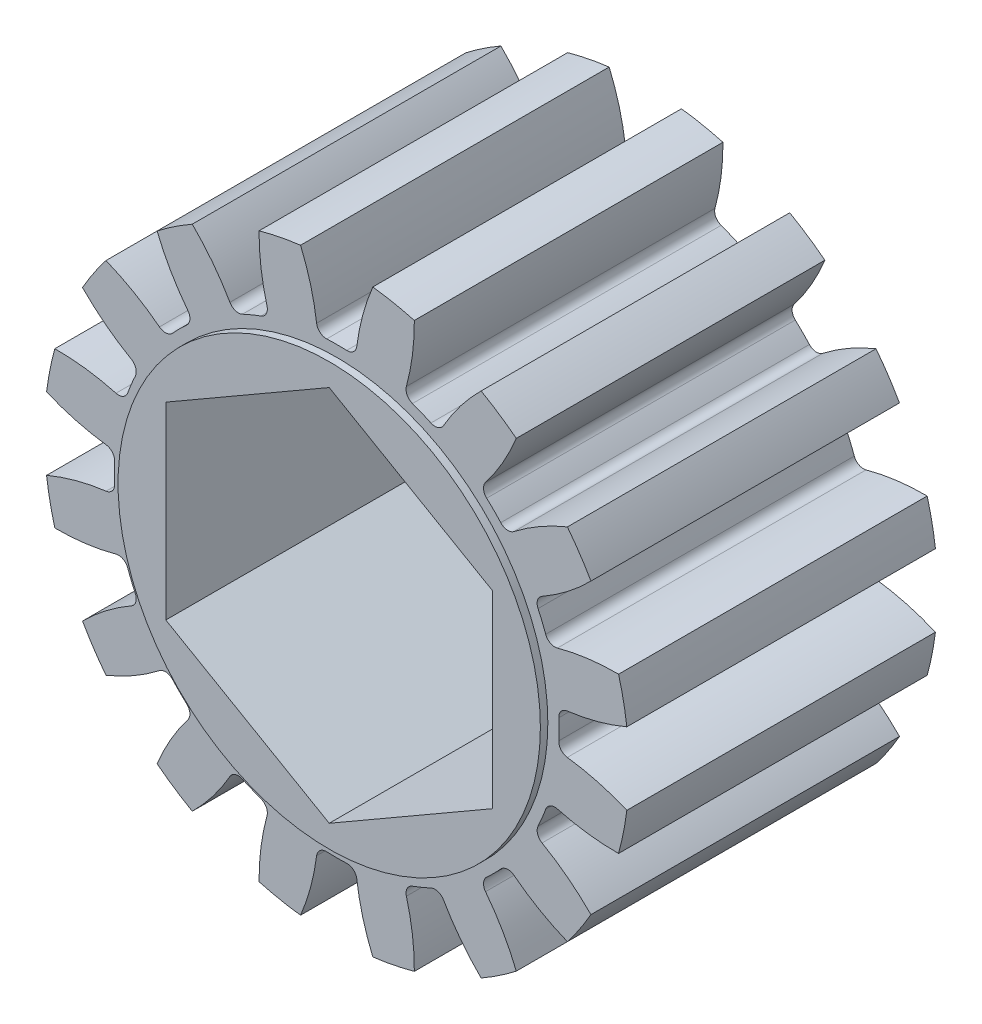
SolidWorks part; units mm, degrees
material "7075-T6 (SN)"
ref_plane "Alzado" through (0, 0, 0) normal (0, 0, 1) x (1, 0, 0)
ref_plane "Planta" through (0, 0, 0) normal (0, 1, 0) x (1, 0, 0)
ref_plane "Vista lateral" through (0, 0, 0) normal (1, 0, 0) x (0, 0, -1)
sketch "Croquis1" plane through (0, 0, 0) normal (0, 0, 1) x (1, 0, 0)
  circle A0 centre (0, 0) radius 10.16 construction
  circle A1 centre (0, 0) radius 11.43
extrude "Saliente-Extruir1" add sketch "Croquis1" along normal mid plane 12.065
sketch "Croquis2" plane through (0, 0, 0) normal (0, 0, 1) x (1, 0, 0)
  line L0 (0, 0) -> (0, 11.43) construction
  line L1 (0, 0) -> (4.3741, 10.5599) construction
  line L2 (0, 0) -> (2.2299, 11.2104) construction
  line L3 (-0.7471, 8.6584) -> (0, 0) construction
  line L4 (-0.9959, 10.1111) -> (0.9959, 10.1111) construction
  line L5 (0.9959, 10.1111) -> (2.9493, 9.7225) construction
  line L6 (-1.3173, 11.3538) -> (0, 6.2604) construction
  circle A0 centre (0, 0) radius 11.43 construction
  arc A2 (0.7471, 8.6584) -> (-0.7471, 8.6584) centre (0, 0) ccw
  circle A5 centre (0, 0) radius 10.16 construction
  arc A6 (-1.4131, 11.3423) -> (-0.7471, 8.6584) centre (-9.5499, 7.8988) cw
  arc A7 (1.4131, 11.3423) -> (0.7471, 8.6584) centre (9.5499, 7.8988) ccw
  arc A8 (1.4131, 11.3423) -> (-1.4131, 11.3423) centre (0, 0) ccw
  dimension "B" = 1.4694
  dimension "Pressure Angle" = 14.5
extrude "Cortar-Extruir1" cut sketch "Croquis2" against normal through all both and the other way through all
fillet "Redondeo1" radius 0.381 2 edges at (0.7471, 8.6584, 0) (-0.7471, 8.6584, 0)
pattern_circular "MatrizC1" count 16 over 360 about axis through (0, 0, 0) along (0, 0, 1) of "Cortar-Extruir1", "Redondeo1"
sketch "Croquis3" plane through (0, 0, 0) normal (0, 0, 1) x (1, 0, 0)
  circle A0 centre (0, 0) radius 8.255
  dimension "sp" = 16.51
extrude "Saliente-Extruir2" add sketch "Croquis3" along normal mid plane 12.6492
sketch "Croquis4" plane through (0, 0, 0) normal (0, 0, 1) x (1, 0, 0)
  line L1 (0, 7.3763) -> (-6.3881, 3.6882)
  line L2 (-6.3881, 3.6882) -> (-6.3881, -3.6882)
  line L3 (-6.3881, -3.6882) -> (0, -7.3763)
  line L4 (0, -7.3763) -> (6.3881, -3.6882)
  line L5 (6.3881, -3.6882) -> (6.3881, 3.6882)
  line L6 (6.3881, 3.6882) -> (0, 7.3763)
  circle A0 centre (0, 0) radius 6.3881 construction
  dimension "D1" = 12.7762
extrude "Cortar-Extruir2" cut sketch "Croquis4" against normal through all both and the other way through all
equation "\"Number of teeth\" = 16"
equation "\"Diametral Pitch\"= 20"
equation "\"Pressure Angle\"= 14.5"
equation "\"D@Croquis1\"=\"Number of teeth\"/\"Diametral Pitch\""
equation "\"OD@Croquis1\"=(\"Number of teeth\"+2) /\"Diametral Pitch\""
equation "\"D2@Croquis2\"=(360 / \"Number of teeth\")/ 2."
equation "\"D1@Croquis2\"=360 / \"Number of teeth\""
equation "\"B@Croquis2\"=1.157 / \"Diametral Pitch\""
equation "\"Pressure Angle@Croquis2\" = \"Pressure Angle\""
equation "\"D1@Redondeo1\"=(pi / \"Diametral Pitch\") * .0955"
equation "\"D1@MatrizC1\"=\"Number of teeth\""
equation "\"Tt@Saliente-Extruir1\"=if( \"Number of teeth\"=>30,0.375,0.475)"
equation "\"sp@Croquis3\"=if( \"Number of teeth\"=16,0.65,0.7)"
